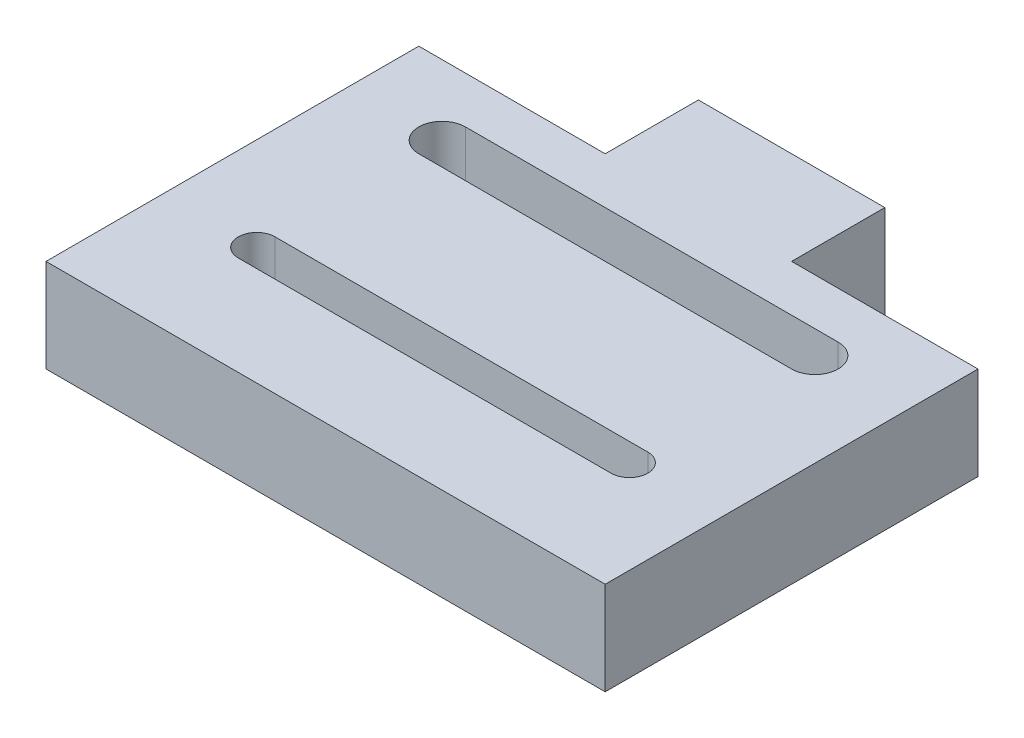
SolidWorks part; units mm, degrees
ref_plane "Front Plane" through (0, 0, 0) normal (0, 0, 1) x (1, 0, 0)
ref_plane "Top Plane" through (0, 0, 0) normal (0, 1, 0) x (1, 0, 0)
ref_plane "Right Plane" through (0, 0, 0) normal (1, 0, 0) x (0, 0, -1)
sketch "Sketch1" plane through (0, 0, 0) normal (0, 0, 1) x (1, 0, 0)
  line L0 (0, -15.6003) -> (0, 0) construction
  line L1 (19.05, -12.6983) -> (-19.05, -12.6983)
  line L2 (19.05, -12.6983) -> (19.05, -6.3483)
  line L3 (19.05, -6.3483) -> (-19.05, -6.3483)
  line L4 (-19.05, -12.6983) -> (-19.05, -6.3483)
  dimension "D1" = 6.35
  dimension "D2" = 38.1
  dimension "D3" = 4.7625
extrude "Boss-Extrude1" add sketch "Sketch1" along normal blind 25.4
sketch "Sketch2" plane through (0, -6.3483, 0) normal (0, 1, 0) x (1, 0, 0)
  line L0 (0, -24.0279) -> (0, -9.3754) construction
  line L1 (12.7, -18.649) -> (-12.7, -18.649)
  line L2 (12.7, -18.649) -> (12.7, -16.149)
  line L3 (12.7, -16.149) -> (-12.7, -16.149)
  line L4 (-12.7, -18.649) -> (-12.7, -16.149)
  line L5 (19.05, -25.4) -> (19.05, 0) construction
  line L6 (-19.05, -25.4) -> (-19.05, 0) construction
  line L7 (15.9392, -17.399) -> (-15.8351, -17.399) construction
  line L8 (19.05, 0) -> (-19.05, 0) construction
  arc A0 (12.7, -18.649) -> (12.7, -16.149) centre (12.7, -17.399) ccw
  arc A1 (-12.7, -18.649) -> (-12.7, -16.149) centre (-12.7, -17.399) cw
  dimension "D1" = 17.399
  dimension "D2" = 2.5
  dimension "D3" = 25.4
extrude "Cut-Extrude1" cut sketch "Sketch2" against normal through all contours L4 L1 L2 L3 | L2 A0 | A1 L4
sketch "Sketch3" plane through (0, 0, 0) normal (0, 0, -1) x (-1, 0, 0)
  line L0 (19.05, -12.6983) -> (-19.05, -12.6983) construction
  line L1 (-6.35, -12.6983) -> (6.35, -12.6983)
  line L2 (-6.35, -12.6983) -> (-6.35, -6.3483)
  line L3 (-6.35, -6.3483) -> (6.35, -6.3483)
  line L4 (6.35, -12.6983) -> (6.35, -6.3483)
  line L5 (-19.05, -6.3483) -> (19.05, -6.3483) construction
  line L6 (0, -12.6983) -> (0, -6.3483) construction
  line L7 (-19.05, -12.6983) -> (-19.05, -6.3483) construction
  line L8 (19.05, -6.3483) -> (19.05, -12.6983) construction
  dimension "D1" = 12.7
extrude "Boss-Extrude4" add sketch "Sketch3" along normal blind 6.35
sketch "Sketch4" plane through (0, -6.3483, 0) normal (0, 1, 0) x (1, 0, 0)
  line L0 (0, -10.4963) -> (0, -1.0151) construction
  line L1 (12.7, -6.35) -> (-12.7, -6.35)
  line L2 (12.7, -6.35) -> (12.7, -3.175)
  line L3 (12.7, -3.175) -> (-12.7, -3.175)
  line L4 (-12.7, -6.35) -> (-12.7, -3.175)
  line L5 (19.05, -25.4) -> (19.05, 0) construction
  line L6 (-19.05, -25.4) -> (-19.05, 0) construction
  line L7 (19.05, 0) -> (6.35, 0) construction
  arc A0 (12.7, -6.35) -> (12.7, -3.175) centre (12.7, -4.7625) ccw
  arc A1 (-12.7, -6.35) -> (-12.7, -3.175) centre (-12.7, -4.7625) cw
  dimension "D1" = 3.175
  dimension "D2" = 3.175
  dimension "D3" = 25.4
extrude "Cut-Extrude2" cut sketch "Sketch4" against normal blind 10 contours L1 L0 L3 L4 | A1 L4 | L0 L1 L2 L3 | L2 A0
